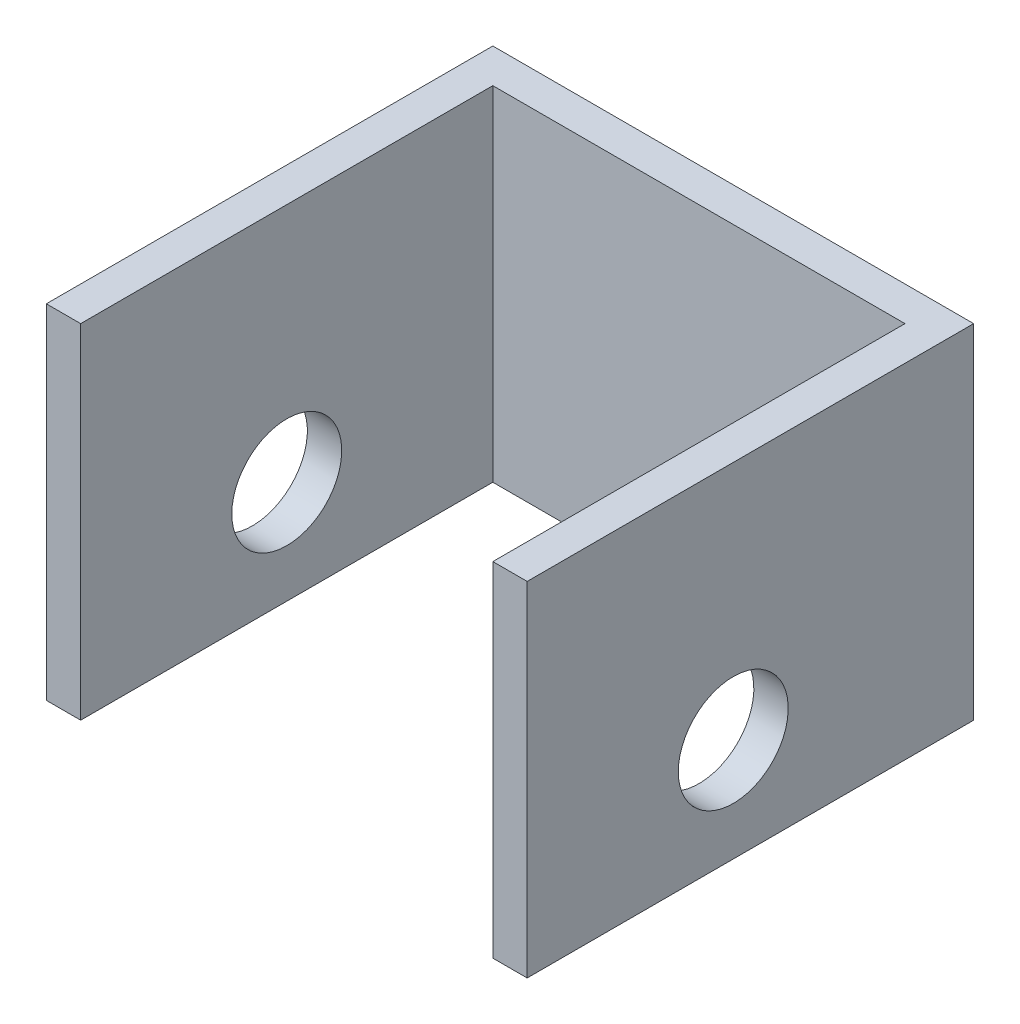
SolidWorks part; units mm, degrees
ref_plane "Plan de face" through (0, 0, 0) normal (0, 0, 1) x (1, 0, 0)
ref_plane "Plan de dessus" through (0, 0, 0) normal (0, 1, 0) x (1, 0, 0)
ref_plane "Plan de droite" through (0, 0, 0) normal (1, 0, 0) x (0, 0, -1)
sketch "Esquisse1" plane through (0, 0, 0) normal (0, 0, 1) x (1, 0, 0)
  line L1 (0, 0) -> (70, 0)
  line L2 (0, 0) -> (0, 50)
  line L3 (0, 50) -> (70, 50)
  line L4 (70, 0) -> (70, 50)
  dimension "D1" = 70
  dimension "D2" = 50
extrude "Boss.-Extru.1" add sketch "Esquisse1" along normal blind 5
sketch "Esquisse2" plane through (0, 0, 5) normal (0, 0, 1) x (1, 0, 0)
  line L0 (0, 0) -> (70, 0) construction
  line L1 (0, 50) -> (5, 50)
  line L2 (0, 50) -> (0, 0)
  line L3 (0, 0) -> (5, 0)
  line L4 (5, 50) -> (5, 0)
  line L5 (35, 50) -> (35, 0) construction
  line L6 (70, 50) -> (0, 50) construction
  line L7 (70, 0) -> (65, 0)
  line L8 (65, 50) -> (65, 0)
  line L9 (70, 50) -> (65, 50)
  line L10 (70, 50) -> (70, 0)
  dimension "D1" = 5
extrude "Boss.-Extru.2" add sketch "Esquisse2" along normal blind 60
sketch "Esquisse3" plane through (0, 0, 0) normal (-1, 0, 0) x (0, 0, 1)
  line L0 (65, 0) -> (0, 0) construction
  line L2 (0, 50) -> (0, 0) construction
  circle A0 centre (35, 15) radius 8
  dimension "D1" = 16
  dimension "D2" = 15
  dimension "D3" = 35
extrude "Enlèv. mat.-Extru.1" cut sketch "Esquisse3" against normal through all
